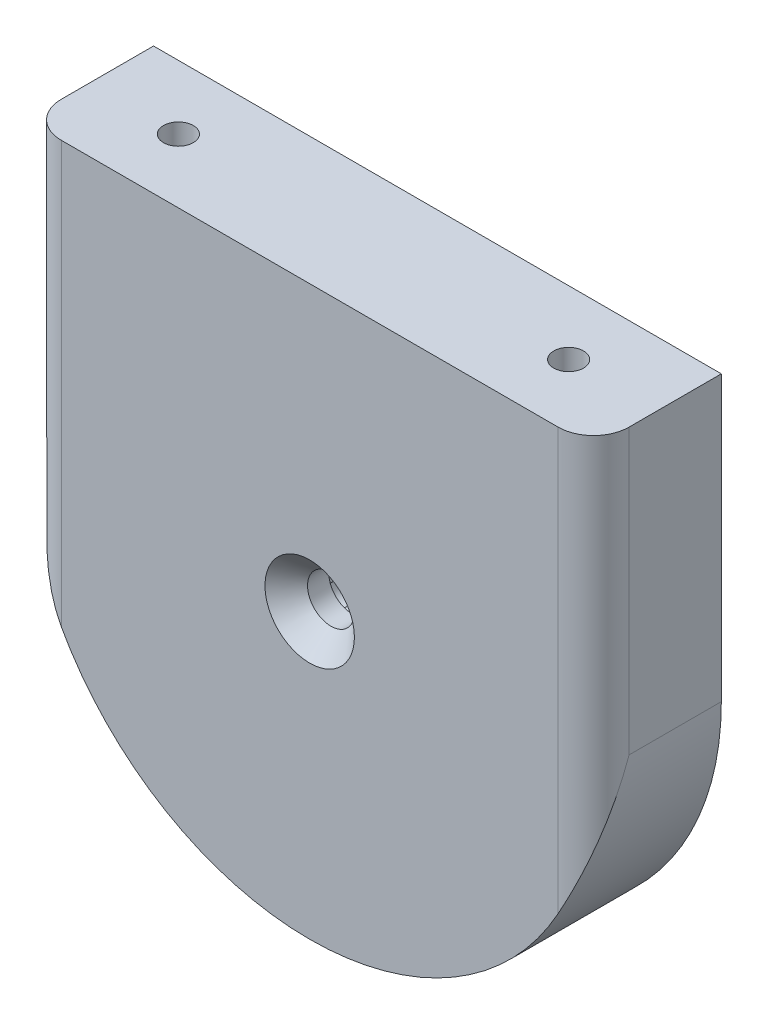
SolidWorks part; units mm, degrees
ref_plane "Plano frontal" through (0, 0, 0) normal (0, 0, 1) x (1, 0, 0)
ref_plane "Plano superior" through (0, 0, 0) normal (0, 1, 0) x (1, 0, 0)
ref_plane "Plano direito" through (0, 0, 0) normal (1, 0, 0) x (0, 0, -1)
sketch "Sketch1" plane through (0, 0, 0) normal (0, 0, 1) x (1, 0, 0)
  line L1 (-8, -8) -> (8, -8)
  line L2 (-8, -8) -> (-8, 8)
  line L3 (-8, 8) -> (8, 8)
  line L4 (8, -8) -> (8, 8)
  line L5 (-8, -8) -> (8, 8) construction
  line L6 (-8, 8) -> (8, -8) construction
  line L7 (40, -40) -> (-40, -40)
  line L8 (40, -40) -> (40, 40)
  line L9 (40, 40) -> (-40, 40)
  line L10 (-40, -40) -> (-40, 40)
  line L11 (40, -40) -> (-40, 40) construction
  line L12 (40, 40) -> (-40, -40) construction
  circle A0 centre (-8, 8) radius 2
  circle A1 centre (8, 8) radius 2
  circle A2 centre (8, -8) radius 2
  circle A3 centre (-8, -8) radius 2
  point P0 (0, 0)
  point P10 (0, 0)
  dimension "D2" = 4
  dimension "D1" = 16
  dimension "D3" = 80
  dimension "D4" = 80
extrude "Boss-Extrude1" add sketch "Sketch1" along normal blind 12 contours L10 L7 L8 L9 A3 L2 A0 L3 A1 L4 A2 L1
sketch "Sketch2" plane through (0, 0, 12) normal (0, 0, 1) x (1, 0, 0)
  line L4 (-40, 40) -> (-40, -40)
  line L5 (-40, -40) -> (40, -40)
  line L6 (40, -40) -> (40, 40)
  line L7 (40, 40) -> (-40, 40)
  line L8 (-40, 40) -> (-40, -40)
  line L9 (-40, -40) -> (40, -40)
  line L10 (40, -40) -> (40, 40)
  line L11 (40, 40) -> (-40, 40)
  circle A0 centre (0, 0) radius 1.5
  dimension "D2" = 3
  dimension "D1" = 0
extrude "Boss-Extrude2" add sketch "Sketch2" along normal blind 6
hole_wizard "CSK for M6 Countersunk Flat Head Screw1" positions "Sketch4" profile "Sketch3" countersink size "M6" standard "DIN"
sketch "Sketch4" plane through (0, 0, 18) normal (0, 0, 1) x (1, 0, 0)
  point P0 (0, 0)
sketch "Sketch3" plane through (0, 0, 18) normal (1, 0, 0) x (0, -1, 0)
  line L0 (0, 0) -> (0, 11.9828)
  line L1 (0, 11.9828) -> (3.3, 10)
  line L2 (3.3, 10) -> (3.3, 3)
  line L3 (3.3, 3) -> (6.3, 0)
  line L5 (6.3, 0) -> (0, 0)
  line L6 (-3.3, 3) -> (-6.3, 0) construction
  line L10 (0, 11.9828) -> (-3.3, 10) construction
  line L11 (0, -6.35) -> (0, 107.95) construction
  dimension "Hole Dia." = 6.6
  dimension "Hole Depth" = 10
  dimension "Near C'Sink Dia." = 12.6
  dimension "Near C'Sink Angle" = 90
  dimension "Drill Angle" = 118
fillet "Fillet1" radius 5 2 edges at (-40, 0, 18) (40, 0, 18)
hole_wizard "M5 Tapped Hole1" positions "Sketch6" profile "Sketch5" tap size "M5" standard "DIN"
sketch "Sketch6" plane through (0, 40, 0) normal (0, 1, 0) x (1, 0, 0)
  point P0 (-27.5, -9)
  point P3 (27.5, -9.0126)
sketch "Sketch5" plane through (-27.5, 40, 9) normal (1, 0, 0) x (0, 0, 1)
  line L0 (0, 0) -> (0, 13.6618)
  line L1 (0, 13.6618) -> (2.1, 12.4)
  line L2 (2.1, 12.4) -> (2.1, 0)
  line L5 (2.1, 0) -> (0, 0)
  line L10 (0, 13.6618) -> (-2.1, 12.4) construction
  line L11 (0, -6.35) -> (0, 107.95) construction
  dimension "Tap Drill Dia." = 4.2
  dimension "Tap Drill Depth" = 12.4
  dimension "Drill Angle" = 118
cosmetic thread "Hole Thread1" parameters "D1"=10, "D2"=5
cosmetic thread "Hole Thread2" parameters "D1"=10, "D2"=5
sketch "Sketch7" plane through (0, 0, 18) normal (0, 0, 1) x (1, 0, 0)
  line L0 (-40, 40) -> (-40, -40)
  line L1 (-40, -40) -> (40, -40)
  line L2 (40, -40) -> (40, 40)
  line L3 (40, 40) -> (-40, 40)
  circle A0 centre (0, 0) radius 40
  line M3 (-35, 40) -> (-35, -40)
  line M4 (-35, -40) -> (35, -40)
  line M5 (35, -40) -> (35, 40)
extrude "Cut-Extrude1" cut sketch "Sketch7" against normal through all contours A0 M3 M4 | A0 L0 L1 M3 | A0 L1 M5 | A0 L1 L2 M5
